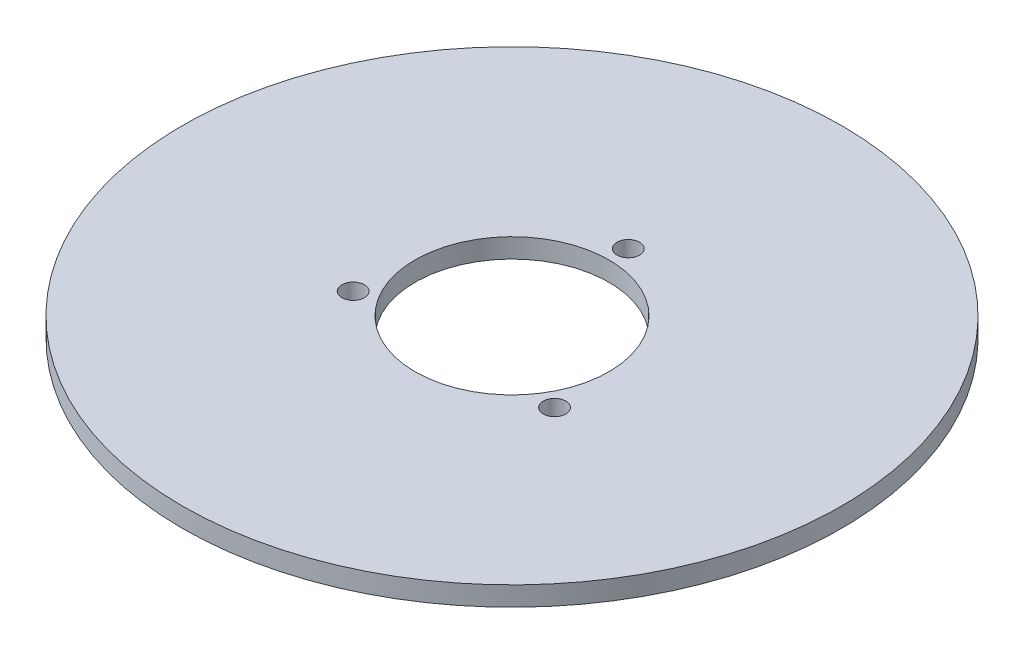
SolidWorks part; units mm, degrees
material "PTFE (geral)"
ref_plane "Plano frontal" through (0, 0, 0) normal (0, 0, 1) x (1, 0, 0)
ref_plane "Plano superior" through (0, 0, 0) normal (0, 1, 0) x (1, 0, 0)
ref_plane "Plano direito" through (0, 0, 0) normal (1, 0, 0) x (0, 0, -1)
sketch "Esboço1" plane through (0, 0, 0) normal (0, 1, 0) x (1, 0, 0)
  circle A0 centre (0, 0) radius 85
  circle A1 centre (0, 30) radius 2.9
  circle A2 centre (25.9808, -15) radius 2.9
  circle A3 centre (-25.9808, -15) radius 2.9
  circle A4 centre (0, 30) radius 2.9 construction
  circle A5 centre (0, 0) radius 25
  circle A6 centre (0, 0) radius 25 construction
  point P11 (0, 0)
  dimension "D1" = 3
  dimension "D2" = 170
extrude "Ressalto-extrusão1" add sketch "Esboço1" along normal blind 5
sketch "Esboço2" plane through (0, 5, 0) normal (0, 1, 0) x (1, 0, 0)
  line L0 (0, -8.1017) -> (0, -408.1017) construction
  circle A0 centre (0, 0) radius 85 construction
  point P0 (0, -85)
